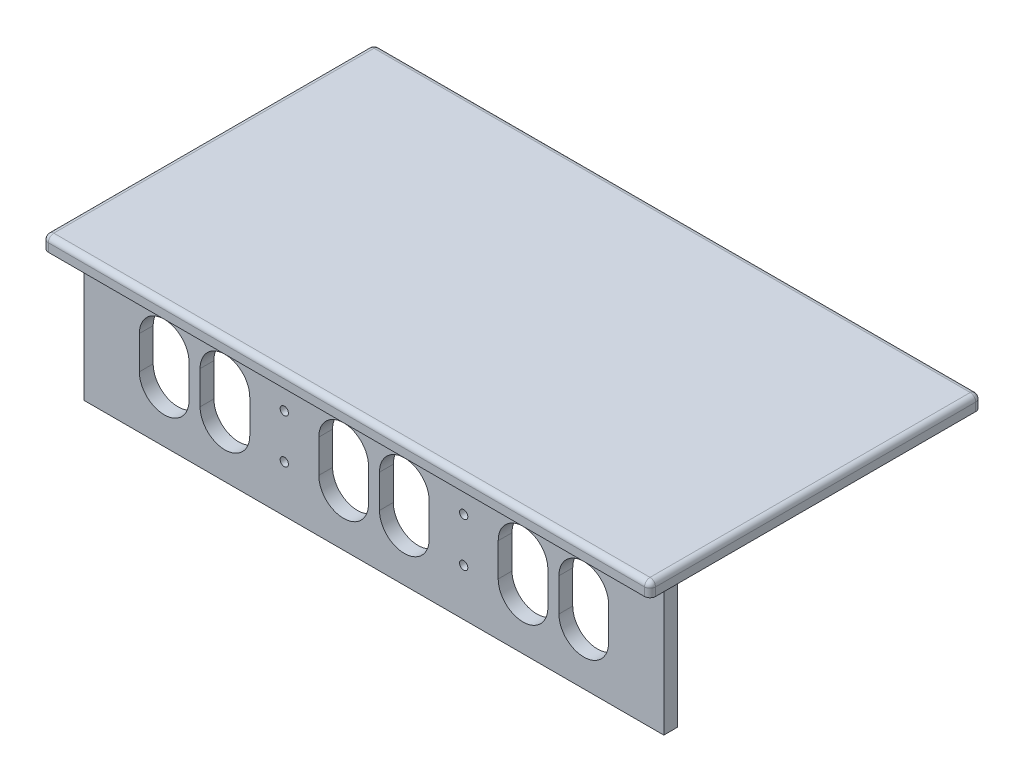
SolidWorks part; units mm, degrees
ref_plane "Alzado" through (0, 0, 0) normal (0, 0, 1) x (1, 0, 0)
ref_plane "Planta" through (0, 0, 0) normal (0, 1, 0) x (1, 0, 0)
ref_plane "Vista lateral" through (0, 0, 0) normal (1, 0, 0) x (0, 0, -1)
sketch "Croquis1" plane through (0, 0, 0) normal (0, 1, 0) x (1, 0, 0)
  line L1 (-110, -60) -> (110, -60)
  line L2 (-110, -60) -> (-110, 60)
  line L3 (-110, 60) -> (110, 60)
  line L4 (110, -60) -> (110, 60)
  line L5 (-110, -60) -> (110, 60) construction
  line L6 (-110, 60) -> (110, -60) construction
  point P0 (0, 0)
  dimension "D1" = 220
  dimension "D2" = 120
extrude "Saliente-Extruir1" add sketch "Croquis1" along normal blind 5
sketch "Croquis2" plane through (0, 0, 0) normal (0, -1, 0) x (1, 0, 0)
  line L1 (-105, 50) -> (105, 50)
  line L2 (-105, 50) -> (-105, 45)
  line L3 (-105, 45) -> (105, 45)
  line L4 (105, 50) -> (105, 45)
  dimension "D1" = 5
  dimension "D2" = 5
  dimension "D3" = 5
  dimension "D4" = 10
extrude "Saliente-Extruir2" add sketch "Croquis2" along normal blind 50
sketch "Croquis3" plane through (0, 0, 50) normal (0, 0, 1) x (1, 0, 0)
  line L0 (-45, -19) -> (-45, -31)
  line L2 (-85, -19) -> (-85, -31)
  line L4 (-67, -19) -> (-67, -31)
  line L5 (-63, -19) -> (-63, -31)
  line L6 (-67, -19) -> (-45, -19) construction
  line L7 (0, -55.7686) -> (0, 27.8957) construction
  line L8 (20, -19) -> (20, -31)
  line L9 (2, -19) -> (2, -31)
  line L10 (-2, -19) -> (-2, -31)
  line L11 (-20, -19) -> (-20, -31)
  line L12 (85, -19) -> (85, -31)
  line L13 (67, -19) -> (67, -31)
  line L14 (63, -19) -> (63, -31)
  line L15 (45, -19) -> (45, -31)
  line L16 (-45, -19) -> (20, -19) construction
  arc A0 (-67, -19) -> (-85, -19) centre (-76, -19) ccw
  arc A1 (-85, -31) -> (-67, -31) centre (-76, -31) ccw
  arc A2 (-63, -31) -> (-45, -31) centre (-54, -31) ccw
  arc A3 (-45, -19) -> (-63, -19) centre (-54, -19) ccw
  arc A4 (2, -31) -> (20, -31) centre (11, -31) ccw
  arc A5 (20, -19) -> (2, -19) centre (11, -19) ccw
  arc A6 (-20, -31) -> (-2, -31) centre (-11, -31) ccw
  arc A7 (-2, -19) -> (-20, -19) centre (-11, -19) ccw
  arc A8 (67, -31) -> (85, -31) centre (76, -31) ccw
  arc A9 (85, -19) -> (67, -19) centre (76, -19) ccw
  arc A10 (45, -31) -> (63, -31) centre (54, -31) ccw
  arc A11 (63, -19) -> (45, -19) centre (54, -19) ccw
  point P17 (-76, -10)
  point P18 (-76, -40)
  point P20 (-22.3327, -25)
  point P27 (0, 0)
  point P50 (0, 0)
  point P51 (0, 0)
  point P52 (0, 0)
  dimension "D1" = 30
  dimension "D3" = 2
  dimension "D6" = 9
  dimension "D2" = 20
  dimension "D4" = 22
  dimension "D5" = 10
  dimension "D7" = 18
  dimension "D8" = 12
  dimension "D9" = 3
  dimension "D10" = 65
  dimension "D11" = 20
extrude "Cortar-Extruir1" cut sketch "Croquis3" against normal up to next
fillet "Redondeo1" radius 2 8 edges at (-110, 2.5, 60) (110, 2.5, 60) (0, 5, 60) (-110, 5, 0) (0, 5, -60) (110, 5, 0) (-110, 2.5, -60) (110, 2.5, -60)
hole_wizard "Avellanado para tornillo con cabeza plana de M21" positions "Croquis8" profile "Croquis10" countersink size "M2" standard "Ansi Metric"
sketch "Croquis8" plane through (0, 5, 0) normal (0, 1, 0) x (1, 0, 0)
  arc A0 (108, -60) -> (110, -58) centre (108, -58) ccw construction
  point P0 (-107.5, -57.5)
  point P2 (-107.5, 57.5)
  point P4 (107.5, 57.5)
  point P6 (107.5, -57.5)
  point P16 (0, 0)
  point P17 (0, 0)
  point P18 (0, 0)
  point P19 (0, 0)
  point P22 (110, -58)
  point P28 (108, -60)
  point P32 (108, -60)
  dimension "D1" = 2.5
  dimension "D2" = 2.5
  dimension "D3" = 2.5
  dimension "D4" = 2.5
sketch "Croquis10" plane through (-107.5, 5, 57.5) normal (1, 0, 0) x (0, 0, 1)
  line L0 (0, 0) -> (0, 10.721)
  line L1 (0, 10.721) -> (1.2, 10)
  line L2 (1.2, 10) -> (1.2, 1)
  line L3 (1.2, 1) -> (2.2, 0)
  line L5 (2.2, 0) -> (0, 0)
  line L6 (-1.2, 1) -> (-2.2, 0) construction
  line L10 (0, 10.721) -> (-1.2, 10) construction
  line L11 (0, -6.35) -> (0, 107.95) construction
  dimension "Diámetro de taladro" = 2.4
  dimension "Profundidad de taladro" = 10
  dimension "Ángulo de avellanado cercano" = 4.4
  dimension "Ángulo de avellanado lejano" = 90
  dimension "Ángulo de perforador" = 118
sketch "Croquis11" plane through (0, 0, 50) normal (0, 0, 1) x (1, 0, 0)
  line L0 (-45, -25) -> (-20, -25) construction
  line L1 (-45, -31) -> (-45, -19) construction
  line L2 (-20, -19) -> (-20, -31) construction
  line L3 (-32.5, -25) -> (-32.5, -9) construction
  line L4 (0, -1.2539) -> (0, -56.1662) construction
  circle A0 centre (-32.5, -17) radius 1.5
  circle A1 centre (-32.5, -33) radius 1.5
  circle A2 centre (32.5, -17) radius 1.5
  circle A3 centre (32.5, -33) radius 1.5
  dimension "D1" = 3
  dimension "D2" = 8
extrude "Cortar-Extruir3" cut sketch "Croquis11" against normal up to next
